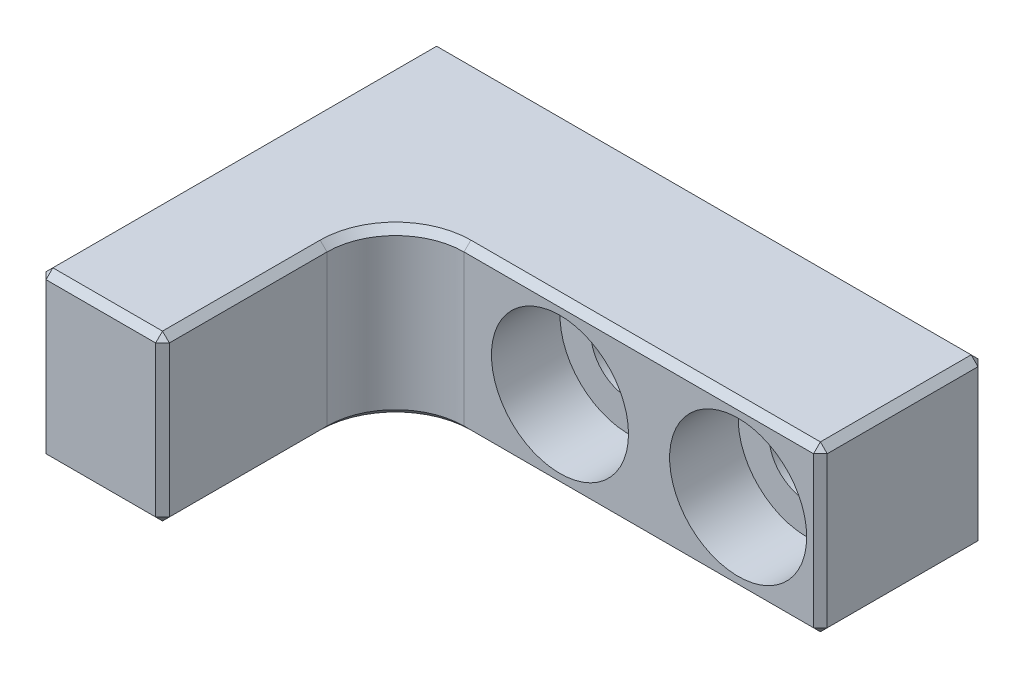
SolidWorks part; units mm, degrees
ref_plane "前视基准面" through (0, 0, 0) normal (0, 0, 1) x (1, 0, 0)
ref_plane "上视基准面" through (0, 0, 0) normal (0, 1, 0) x (1, 0, 0)
ref_plane "右视基准面" through (0, 0, 0) normal (1, 0, 0) x (0, 0, -1)
sketch "草图1" plane through (0, 0, 0) normal (0, 0, 1) x (1, 0, 0)
  line L1 (0, 0) -> (40, 0)
  line L2 (0, 0) -> (0, 12)
  line L3 (0, 12) -> (40, 12)
  line L4 (40, 0) -> (40, 12)
  dimension "D1" = 12
  dimension "D2" = 40
extrude "凸台-拉伸1" add sketch "草图1" along normal blind 12
sketch "草图2" plane through (0, 0, 12) normal (0, 0, 1) x (1, 0, 0)
  line L0 (0, 0) -> (40, 0) construction
  line L1 (0, 12) -> (9, 12)
  line L2 (0, 12) -> (0, 0)
  line L3 (0, 0) -> (9, 0)
  line L4 (9, 12) -> (9, 0)
  dimension "D1" = 9
extrude "凸台-拉伸2" add sketch "草图2" along normal blind 17
fillet "圆角1" radius 5 1 edges
hole_wizard "M5 六角凹头螺钉的柱形沉头孔1" positions "草图6" profile "草图5" counterbore size "M5" standard "ISO" end condition through all
sketch "草图6" plane through (0, 0, 12) normal (0, 0, 1) x (1, 0, 0)
  line L0 (40, 12) -> (14, 12) construction
  line L1 (40, 0) -> (40, 12) construction
  point P0 (34, 6)
  point P11 (21, 6)
  dimension "D1" = 6
  dimension "D2" = 6
  dimension "D3" = 2
sketch "草图5" plane through (34, 6, 12) normal (1, 0, 0) x (0, -1, 0)
  line L0 (0, 0) -> (0, 12)
  line L1 (0, 12) -> (2.75, 12)
  line L3 (2.75, 12) -> (2.75, 5)
  line L4 (2.75, 5) -> (5, 5)
  line L5 (5, 5) -> (5, 0)
  line L7 (5, 0) -> (0, 0)
  line L11 (0, -6.35) -> (0, 107.95) construction
  dimension "通孔孔直径" = 5.5
  dimension "通孔孔深度" = 12
  dimension "柱形沉头孔直径" = 10
  dimension "柱形沉头孔深度" = 5
chamfer "倒角1" distance 0.5 angle 45 19 edges at (9, 6, 29) (0, 6, 29) (40, 6, 12) (40, 6, 0) (40, 12, 6) (10.4645, 12, 13.4645) (4.5, 12, 29) (0, 12, 14.5) (20, 12, 0) (0, 0, 14.5) (4.5, 0, 29) (10.4645, 0, 13.4645) (40, 0, 6) (20, 0, 0) (0, 6, 0)
